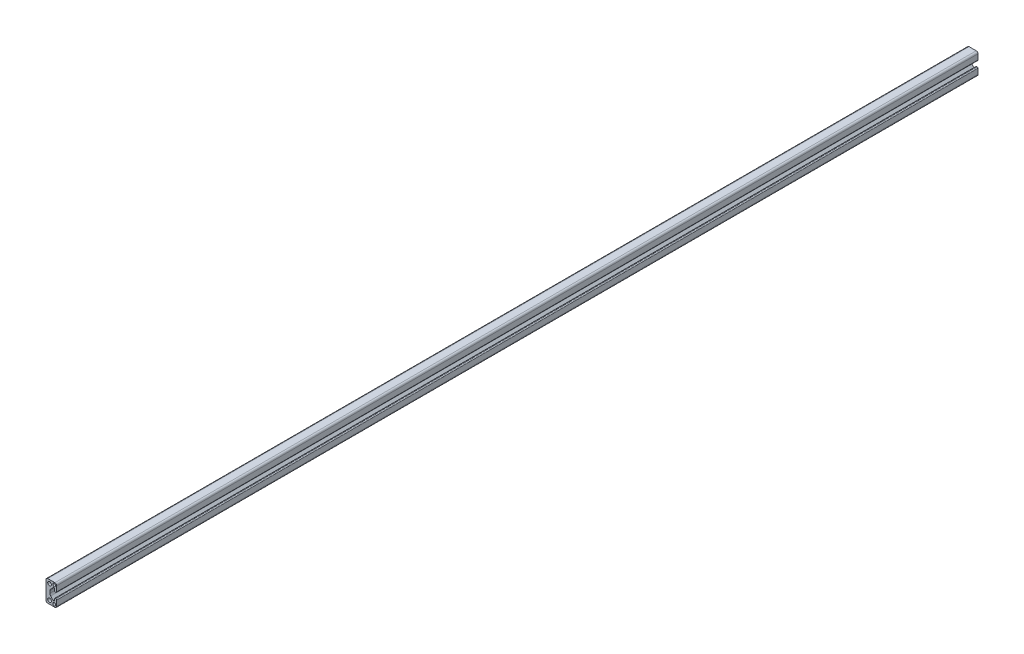
SolidWorks part; units mm, degrees
ref_plane "Front Plane" through (0, 0, 0) normal (0, 0, 1) x (1, 0, 0)
ref_plane "Top Plane" through (0, 0, 0) normal (0, 1, 0) x (1, 0, 0)
ref_plane "Right Plane" through (0, 0, 0) normal (1, 0, 0) x (0, 0, -1)
sketch "Sketch1" plane through (0, 0, 0) normal (0, 0, 1) x (1, 0, 0)
  line L0 (-6.35, 0) -> (6.35, 0) construction
  line L1 (6.35, 4.3011) -> (6.35, 10.5833)
  line L2 (4.2333, 12.7) -> (-4.2333, 12.7)
  line L3 (-6.35, 10.5833) -> (-6.35, 0)
  line L4 (-1.778, 0) -> (-1.778, 1.27)
  line L5 (-0.8467, 3.5339) -> (2.4133, 6.7939)
  line L6 (2.7725, 6.9427) -> (3.048, 6.9427)
  line L7 (3.6407, 6.35) -> (3.6407, 4.3011)
  line L8 (4.6905, 3.2512) -> (5.3001, 3.2512)
  circle A2 centre (3.429, 9.906) radius 1.6933
  circle A3 centre (-2.1167, 8.4667) radius 2.2013
  arc A4 (6.35, 10.5833) -> (4.2333, 12.7) centre (4.2333, 10.5833) ccw
  arc A5 (-4.2333, 12.7) -> (-6.35, 10.5833) centre (-4.2333, 10.5833) ccw
  arc A6 (-0.8467, 3.5339) -> (-1.778, 1.27) centre (1.4393, 1.27) ccw
  arc A7 (2.7725, 6.9427) -> (2.4133, 6.7939) centre (2.7725, 6.4347) ccw
  arc A8 (3.6407, 6.35) -> (3.048, 6.9427) centre (3.048, 6.35) ccw
  arc A9 (3.6407, 4.3011) -> (4.6905, 3.2512) centre (4.6905, 4.3011) ccw
  arc A10 (5.3001, 3.2512) -> (6.35, 4.3011) centre (5.3001, 4.3011) ccw
  dimension "D8" = 2.1167
  dimension "D9" = 3.3867
  dimension "D10" = 4.4027
  dimension "D13" = 1.0499
  dimension "D14" = 3.2173
  dimension "D16" = 0.508
  dimension "D17" = 0.5927
  dimension "Rail Height" = 25.4
  dimension "Rail Width" = 12.7
  dimension "D1" = 4.572
  dimension "D2" = 135
  dimension "D3" = 1.27
  dimension "D4" = 16.9333
  dimension "D5" = 4.2333
  dimension "D7" = 2.921
  dimension "D6" = 19.812
  dimension "TSlot Wdith" = 6.5024
  dimension "D11" = 2.7093
  dimension "D12" = 6.9427
  dimension "D15" = 5.5033
sketch "Sketch2" plane through (0, 0, 0) normal (1, 0, 0) x (0, 0, -1)
  line L0 (-914.4, 0) -> (914.4, 0)
  point P2 (-876.3, 0)
  point P3 (876.3, 0)
  dimension "Length" = 1828.8
  dimension "D1" = 38.1
  dimension "D2" = 38.1
sketch "Sketch3" plane through (0, 0, 0) normal (0, 0, 1) x (1, 0, 0)
  line L0 (-1.778, 0) -> (-1.778, 1.27) construction
  line L1 (-0.8467, 3.5339) -> (2.4133, 6.7939) construction
  line L2 (2.7725, 6.9427) -> (3.048, 6.9427) construction
  line L3 (3.6407, 6.35) -> (3.6407, 4.3011) construction
  line L4 (4.6905, 3.2512) -> (5.3001, 3.2512) construction
  line L5 (6.35, 4.3011) -> (6.35, 10.5833) construction
  line L6 (4.2333, 12.7) -> (-4.2333, 12.7) construction
  line L7 (-6.35, 10.5833) -> (-6.35, 0) construction
  line L8 (-1.778, 0) -> (-1.778, 1.27)
  line L9 (-0.8467, 3.5339) -> (2.4133, 6.7939)
  line L10 (2.7725, 6.9427) -> (3.048, 6.9427)
  line L11 (3.6407, 6.35) -> (3.6407, 4.3011)
  line L12 (4.6905, 3.2512) -> (5.3001, 3.2512)
  line L13 (6.35, 4.3011) -> (6.35, 10.5833)
  line L14 (4.2333, 12.7) -> (-4.2333, 12.7)
  line L15 (-6.35, 10.5833) -> (-6.35, 0)
  line L16 (-6.35, 0) -> (-1.778, 0)
  arc A0 (-0.8467, 3.5339) -> (-1.778, 1.27) centre (1.4393, 1.27) ccw construction
  circle A1 centre (-2.1167, 8.4667) radius 2.2013
  circle A2 centre (-2.1167, 8.4667) radius 2.2013
  circle A3 centre (3.429, 9.906) radius 1.6933
  circle A4 centre (3.429, 9.906) radius 1.6933
  arc A5 (2.7725, 6.9427) -> (2.4133, 6.7939) centre (2.7725, 6.4347) ccw construction
  arc A6 (3.6407, 6.35) -> (3.048, 6.9427) centre (3.048, 6.35) ccw construction
  arc A7 (3.6407, 4.3011) -> (4.6905, 3.2512) centre (4.6905, 4.3011) ccw construction
  arc A8 (5.3001, 3.2512) -> (6.35, 4.3011) centre (5.3001, 4.3011) ccw construction
  arc A9 (6.35, 10.5833) -> (4.2333, 12.7) centre (4.2333, 10.5833) ccw construction
  arc A10 (-4.2333, 12.7) -> (-6.35, 10.5833) centre (-4.2333, 10.5833) ccw construction
  arc A11 (-0.8467, 3.5339) -> (-1.778, 1.27) centre (1.4393, 1.27) ccw
  arc A12 (2.7725, 6.9427) -> (2.4133, 6.7939) centre (2.7725, 6.4347) ccw
  arc A13 (3.6407, 6.35) -> (3.048, 6.9427) centre (3.048, 6.35) ccw
  arc A14 (3.6407, 4.3011) -> (4.6905, 3.2512) centre (4.6905, 4.3011) ccw
  arc A15 (5.3001, 3.2512) -> (6.35, 4.3011) centre (5.3001, 4.3011) ccw
  arc A16 (6.35, 10.5833) -> (4.2333, 12.7) centre (4.2333, 10.5833) ccw
  arc A17 (-4.2333, 12.7) -> (-6.35, 10.5833) centre (-4.2333, 10.5833) ccw
  dimension "D1" = 0
  dimension "D2" = 0
extrude "Boss-Extrude1" add sketch "Sketch3" along normal mid plane 1828.8
mirror "Mirror1" about plane through (0, 0, 0) normal (0, 1, 0) of bodies 104
sketch "Sketch4" plane through (0, 0, 914.4) normal (0, 0, 1) x (1, 0, 0)
  line L14 (-6.35, 10.5833) -> (-6.35, -10.5833)
  line L15 (-4.2333, -12.7) -> (4.2333, -12.7)
  line L16 (6.35, -10.5833) -> (6.35, -4.3011)
  line L17 (5.3001, -3.2512) -> (4.6905, -3.2512)
  line L18 (3.6407, -4.3011) -> (3.6407, -6.35)
  line L19 (3.048, -6.9427) -> (2.7725, -6.9427)
  line L20 (2.4133, -6.7939) -> (-0.8467, -3.5339)
  line L21 (-1.778, -1.27) -> (-1.778, 1.27)
  line L22 (-0.8467, 3.5339) -> (2.4133, 6.7939)
  line L23 (2.7725, 6.9427) -> (3.048, 6.9427)
  line L24 (3.6407, 6.35) -> (3.6407, 4.3011)
  line L25 (4.6905, 3.2512) -> (5.3001, 3.2512)
  line L26 (6.35, 4.3011) -> (6.35, 10.5833)
  line L27 (4.2333, 12.7) -> (-4.2333, 12.7)
  line L28 (-6.35, 10.5833) -> (-6.35, -10.5833)
  line L29 (-4.2333, -12.7) -> (4.2333, -12.7)
  line L30 (6.35, -10.5833) -> (6.35, -4.3011)
  line L31 (5.3001, -3.2512) -> (4.6905, -3.2512)
  line L32 (3.6407, -4.3011) -> (3.6407, -6.35)
  line L33 (3.048, -6.9427) -> (2.7725, -6.9427)
  line L34 (2.4133, -6.7939) -> (-0.8467, -3.5339)
  line L35 (-1.778, -1.27) -> (-1.778, 1.27)
  line L36 (-0.8467, 3.5339) -> (2.4133, 6.7939)
  line L37 (2.7725, 6.9427) -> (3.048, 6.9427)
  line L38 (3.6407, 6.35) -> (3.6407, 4.3011)
  line L39 (4.6905, 3.2512) -> (5.3001, 3.2512)
  line L40 (6.35, 4.3011) -> (6.35, 10.5833)
  line L41 (4.2333, 12.7) -> (-4.2333, 12.7)
  arc A14 (-6.35, -10.5833) -> (-4.2333, -12.7) centre (-4.2333, -10.5833) ccw
  arc A15 (4.2333, -12.7) -> (6.35, -10.5833) centre (4.2333, -10.5833) ccw
  arc A16 (6.35, -4.3011) -> (5.3001, -3.2512) centre (5.3001, -4.3011) ccw
  arc A17 (4.6905, -3.2512) -> (3.6407, -4.3011) centre (4.6905, -4.3011) ccw
  arc A18 (3.048, -6.9427) -> (3.6407, -6.35) centre (3.048, -6.35) ccw
  arc A19 (2.4133, -6.7939) -> (2.7725, -6.9427) centre (2.7725, -6.4347) ccw
  arc A20 (-1.778, -1.27) -> (-0.8467, -3.5339) centre (1.4393, -1.27) ccw
  arc A21 (-0.8467, 3.5339) -> (-1.778, 1.27) centre (1.4393, 1.27) ccw
  arc A22 (2.7725, 6.9427) -> (2.4133, 6.7939) centre (2.7725, 6.4347) ccw
  arc A23 (3.6407, 6.35) -> (3.048, 6.9427) centre (3.048, 6.35) ccw
  arc A24 (3.6407, 4.3011) -> (4.6905, 3.2512) centre (4.6905, 4.3011) ccw
  arc A25 (5.3001, 3.2512) -> (6.35, 4.3011) centre (5.3001, 4.3011) ccw
  arc A26 (6.35, 10.5833) -> (4.2333, 12.7) centre (4.2333, 10.5833) ccw
  arc A27 (-4.2333, 12.7) -> (-6.35, 10.5833) centre (-4.2333, 10.5833) ccw
  arc A28 (-6.35, -10.5833) -> (-4.2333, -12.7) centre (-4.2333, -10.5833) ccw
  arc A29 (4.2333, -12.7) -> (6.35, -10.5833) centre (4.2333, -10.5833) ccw
  arc A30 (6.35, -4.3011) -> (5.3001, -3.2512) centre (5.3001, -4.3011) ccw
  arc A31 (4.6905, -3.2512) -> (3.6407, -4.3011) centre (4.6905, -4.3011) ccw
  arc A32 (3.048, -6.9427) -> (3.6407, -6.35) centre (3.048, -6.35) ccw
  arc A33 (2.4133, -6.7939) -> (2.7725, -6.9427) centre (2.7725, -6.4347) ccw
  arc A34 (-1.778, -1.27) -> (-0.8467, -3.5339) centre (1.4393, -1.27) ccw
  arc A35 (-0.8467, 3.5339) -> (-1.778, 1.27) centre (1.4393, 1.27) ccw
  arc A36 (2.7725, 6.9427) -> (2.4133, 6.7939) centre (2.7725, 6.4347) ccw
  arc A37 (3.6407, 6.35) -> (3.048, 6.9427) centre (3.048, 6.35) ccw
  arc A38 (3.6407, 4.3011) -> (4.6905, 3.2512) centre (4.6905, 4.3011) ccw
  arc A39 (5.3001, 3.2512) -> (6.35, 4.3011) centre (5.3001, 4.3011) ccw
  arc A40 (6.35, 10.5833) -> (4.2333, 12.7) centre (4.2333, 10.5833) ccw
  arc A41 (-4.2333, 12.7) -> (-6.35, 10.5833) centre (-4.2333, 10.5833) ccw
  dimension "D1" = 0
extrude "Cut-Extrude1" cut sketch "Sketch4" against normal blind 733.425
equation "\"D1@Sketch1\"=\"Rail Width@Sketch1\"*0.36"
equation "\"D3@Sketch1\"=\"Rail Height@Sketch1\"*0.05"
equation "\"D4@Sketch1\"=\"Rail Height@Sketch1\"*2/3"
equation "\"D5@Sketch1\"=\"D4@Sketch1\"*1/4"
equation "\"D7@Sketch1\"=\"Rail Width@Sketch1\"*0.23"
equation "\"D6@Sketch1\"=\"Rail Height@Sketch1\"*0.78"
equation "\"D8@Sketch1\"=\"D4@Sketch1\"*1/8"
equation "\"D9@Sketch1\"=\"D4@Sketch1\"*1/5"
equation "\"D10@Sketch1\"=\"D4@Sketch1\"*0.26"
equation "\"D11@Sketch1\"=\"D4@Sketch1\"*0.16"
equation "\"D12@Sketch1\"=\"D4@Sketch1\"*0.41"
equation "\"D13@Sketch1\"=\"D4@Sketch1\"*0.062"
equation "\"D14@Sketch1\"=\"D9@Sketch1\"*0.95"
equation "\"D15@Sketch1\"=\"D4@Sketch1\"*0.325"
equation "\"D16@Sketch1\"=\"D4@Sketch1\"*0.03"
equation "\"D17@Sketch1\"=\"D4@Sketch1\"*0.035"
equation "\"D2@Sketch2\"=\"D1@Sketch2\""
equation "\"D1@Boss-Extrude1\"=\"length@sketch2\""
